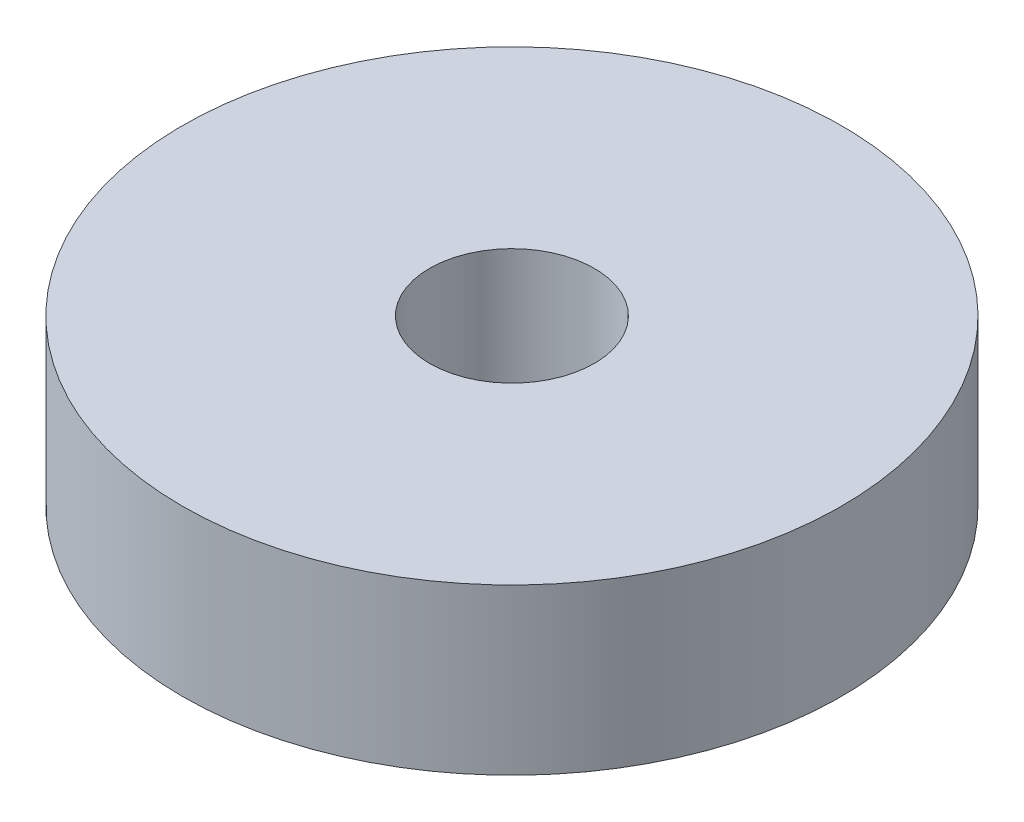
SolidWorks part; units mm, degrees
ref_plane "前视基准面" through (0, 0, 0) normal (0, 0, 1) x (1, 0, 0)
ref_plane "上视基准面" through (0, 0, 0) normal (0, 1, 0) x (1, 0, 0)
ref_plane "右视基准面" through (0, 0, 0) normal (1, 0, 0) x (0, 0, -1)
other "Configuration Table"
sketch "草图1" plane through (0, 0, 0) normal (0, 1, 0) x (1, 0, 0)
  circle A0 centre (0, 0) radius 10
  circle A1 centre (0, 0) radius 2.5
  dimension "D1" = 20
  dimension "D2" = 5
extrude "凸台-拉伸1" add sketch "草图1" along normal blind 5
